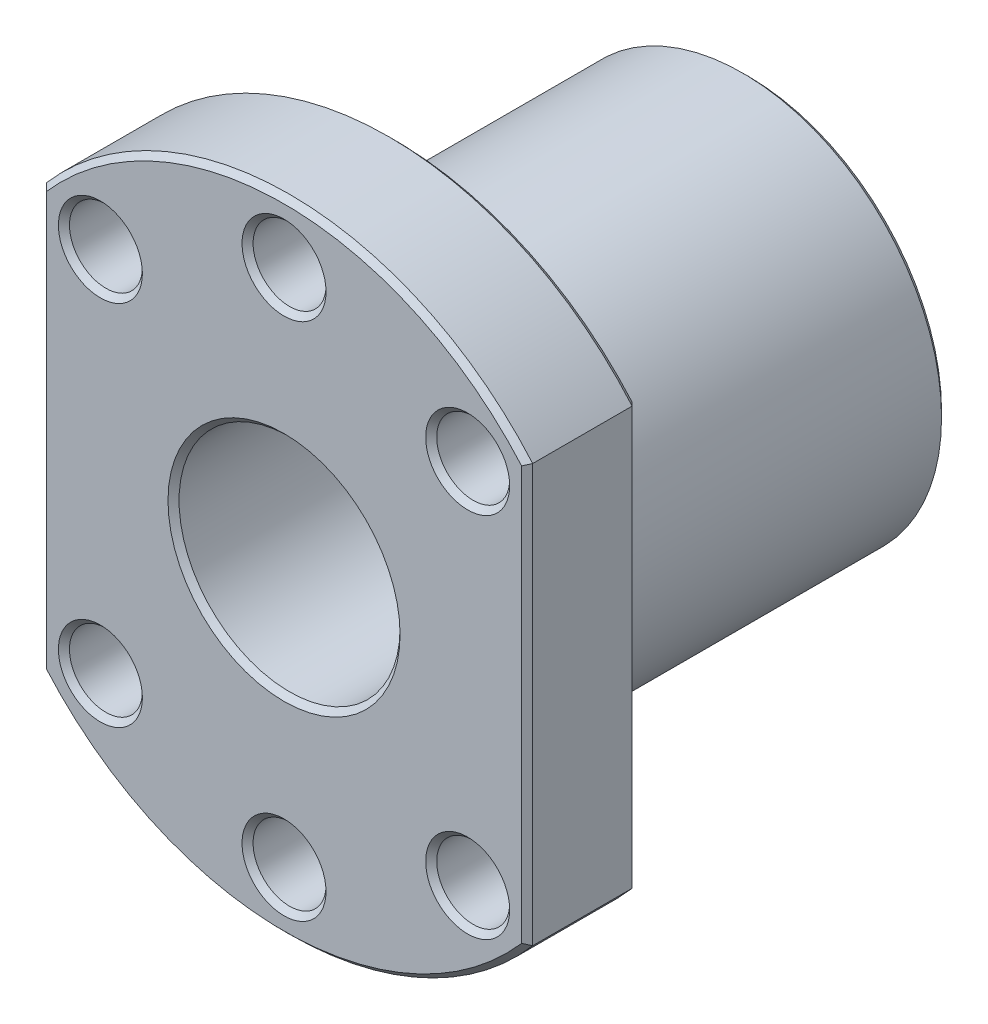
SolidWorks part; units mm, degrees
material "Alloy Steel"
ref_plane "Front Plane" through (0, 0, 0) normal (0, 0, 1) x (1, 0, 0)
ref_plane "Top Plane" through (0, 0, 0) normal (0, 1, 0) x (1, 0, 0)
ref_plane "Right Plane" through (0, 0, 0) normal (1, 0, 0) x (0, 0, -1)
sketch "Sketch1" plane through (0, 0, 0) normal (0, 0, 1) x (0, -1, 0)
  line L1 (-18.8944, 22) -> (18.8944, 22)
  line L3 (-18.8944, -22) -> (18.8944, -22)
  line L5 (-18.8944, 22) -> (18.8944, -22) construction
  line L6 (-18.8944, -22) -> (18.8944, 22) construction
  arc A0 (-18.8944, 22) -> (-18.8944, -22) centre (0, 0) ccw
  circle A1 centre (0, 0) radius 10
  arc A2 (18.8944, -22) -> (18.8944, 22) centre (0, 0) ccw
  circle A3 centre (-23.5, 0) radius 3.3
  circle A4 centre (-16.617, 16.617) radius 3.3
  circle A5 centre (0, 0) radius 23.5 construction
  circle A6 centre (16.617, 16.617) radius 3.3
  circle A7 centre (23.5, 0) radius 3.3
  circle A8 centre (16.617, -16.617) radius 3.3
  circle A10 centre (-16.617, -16.617) radius 3.3
  circle A11 centre (0, 23.5) radius 3.3 [skipped]
  circle A12 centre (0, -23.5) radius 3.3 [skipped]
  dimension "D1" = 29
  dimension "D3" = 23.5
  dimension "D5" = 6.6
  dimension "D6" = 20
  dimension "D2" = 44
  dimension "D4" = 8
extrude "Boss-Extrude1" add sketch "Sketch1" along normal blind 10
cosmetic thread "Cosmetic Thread1" parameters "D2"=23
sketch "Sketch3" plane through (0, 0, 0) normal (0, 0, -1) x (0, -1, 0)
  circle A0 centre (0, 0) radius 18
  circle A1 centre (0, 0) radius 10
  dimension "D1" = 36
  dimension "D2" = 20
extrude "Boss-Extrude2" add sketch "Sketch3" along normal offset from surface (32 mm away) 42 up to face at (-13.317, -16.617, 10)
chamfer "Chamfer1" distance 0.5 angle 45 24 edges at (18, 0, -32) (10, 0, -32) (18, 0, 0) (22, 0, 0) (0, 29, 0) (-22, 0, 0) (0, -29, 0) (3.3, 23.5, 0) (19.917, 16.617, 0) (19.917, -16.617, 0) (3.3, -23.5, 0) (-13.317, -16.617, 0) (-13.317, 16.617, 0) (-13.317, 16.617, 10) (3.3, -23.5, 10) (19.917, 16.617, 10) (-22, 0, 10) (0, 29, 10) (22, 0, 10) (0, -29, 10) (3.3, 23.5, 10) (19.917, -16.617, 10) (-13.317, -16.617, 10) (10, 0, 10)
